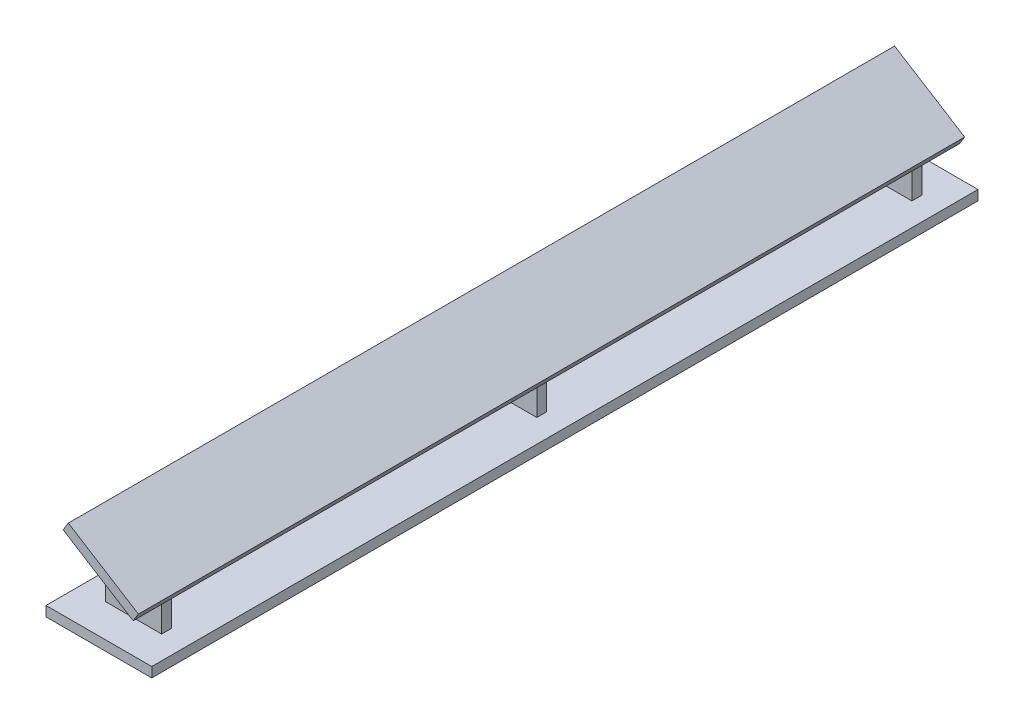
SolidWorks part; units mm, degrees
ref_plane "前视基准面" through (0, 0, 0) normal (0, 0, 1) x (1, 0, 0)
ref_plane "上视基准面" through (0, 0, 0) normal (0, 1, 0) x (1, 0, 0)
ref_plane "右视基准面" through (0, 0, 0) normal (1, 0, 0) x (0, 0, -1)
other "Configuration Table"
sketch "草图1" plane through (0, 0, 0) normal (0, 0, 1) x (1, 0, 0)
  line L0 (940, 0) -> (1004, 0)
  line L1 (1004, 0) -> (1004, 6)
  line L2 (1004, 6) -> (940, 6)
  line L3 (940, 6) -> (940, 0)
extrude "Base_plate_940_to_1004_t6" add sketch "草图1" along normal blind 500 separate body
sketch "草图2" plane through (0, 0, 0) normal (0, 0, 1) x (1, 0, 0)
  line L0 (953.526, 55.9366) -> (995.9284, 29.4407)
  line L1 (995.9284, 29.4407) -> (992.7489, 24.3524)
  line L2 (992.7489, 24.3524) -> (950.3465, 50.8483)
  line L3 (950.3465, 50.8483) -> (953.526, 55.9366)
extrude "Inclined_bearing_plate_t6" add sketch "草图2" along normal blind 500
sketch "草图3" plane through (0, 0, 0) normal (0, 0, 1) x (1, 0, 0)
  line L0 (956, 6) -> (990, 6)
  line L1 (990, 6) -> (990, 26.0701)
  line L2 (990, 26.0701) -> (956, 47.3156)
  line L3 (956, 47.3156) -> (956, 6)
extrude "Toe_web_1_t6" add sketch "草图3" along normal blind 6 from offset 20
sketch "草图4" plane through (0, 0, 0) normal (0, 0, 1) x (1, 0, 0)
  line L0 (956, 6) -> (990, 6)
  line L1 (990, 6) -> (990, 26.0701)
  line L2 (990, 26.0701) -> (956, 47.3156)
  line L3 (956, 47.3156) -> (956, 6)
extrude "Toe_web_2_t6" add sketch "草图4" along normal blind 6 from offset 247
sketch "草图5" plane through (0, 0, 0) normal (0, 0, 1) x (1, 0, 0)
  line L0 (956, 6) -> (990, 6)
  line L1 (990, 6) -> (990, 26.0701)
  line L2 (990, 26.0701) -> (956, 47.3156)
  line L3 (956, 47.3156) -> (956, 6)
extrude "Toe_web_3_t6" add sketch "草图5" along normal blind 6 from offset 474
